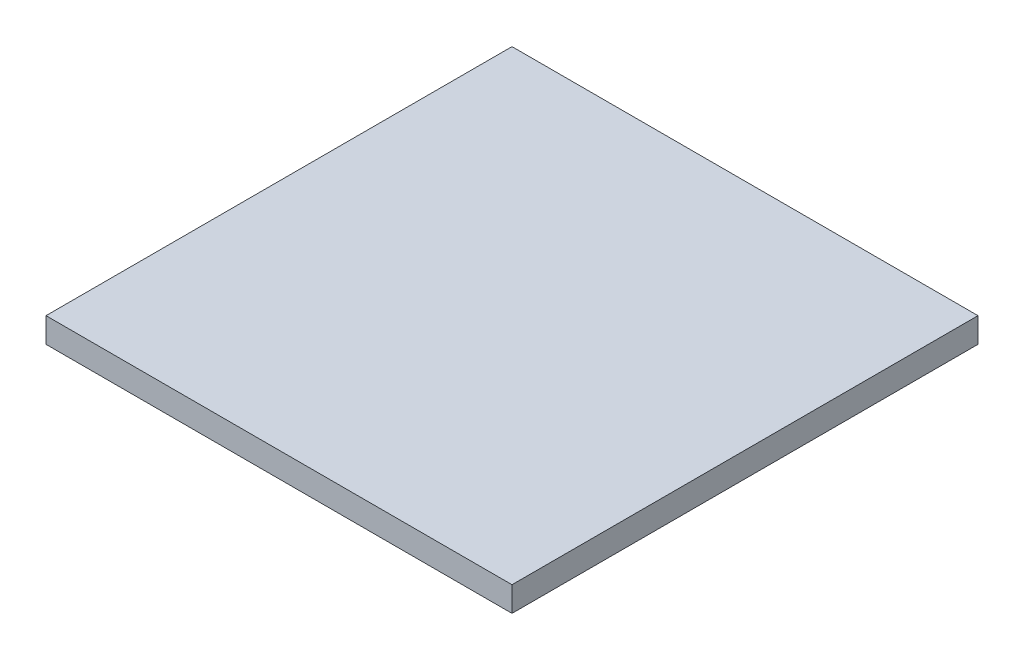
SolidWorks part; units mm, degrees
ref_plane "Front Plane" through (0, 0, 0) normal (0, 0, 1) x (1, 0, 0)
ref_plane "Top Plane" through (0, 0, 0) normal (0, 1, 0) x (1, 0, 0)
ref_plane "Right Plane" through (0, 0, 0) normal (1, 0, 0) x (0, 0, -1)
sketch "Sketch1" plane through (0, 0, 0) normal (0, 1, 0) x (1, 0, 0)
  line L1 (0, 0) -> (-60, 0)
  line L2 (0, 0) -> (0, 60)
  line L3 (0, 60) -> (-60, 60)
  line L4 (-60, 0) -> (-60, 60)
  dimension "D1" = 60
  dimension "D2" = 60
extrude "Top" add sketch "Sketch1" along normal blind 3.2
sketch "Sketch2" [suppressed] plane through (0, 0, 0) normal (0, 1, 0) x (1, 0, 0)
  line L1 (0, 0) -> (25, 0)
  line L2 (0, 0) -> (0, -60)
  line L3 (0, -60) -> (25, -60)
  line L4 (25, 0) -> (25, -60)
  dimension "D1" = 60
  dimension "D2" = 25
extrude "Side" [suppressed] add sketch "Sketch2" along normal blind 3.2
